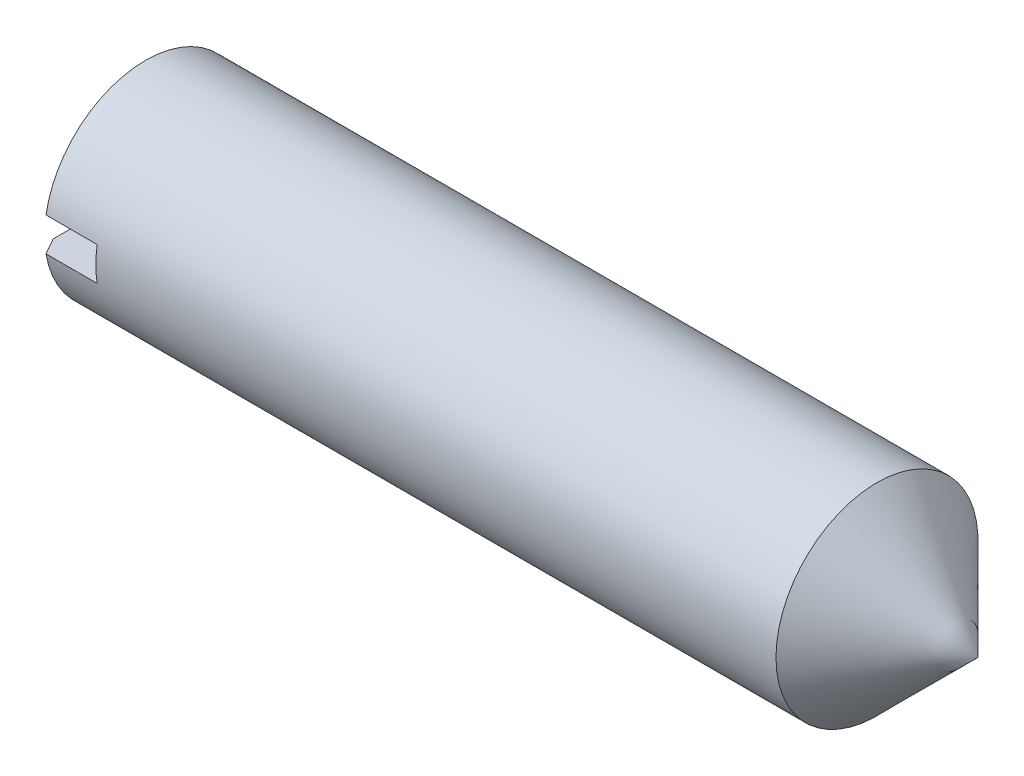
SolidWorks part; units mm, degrees
revolve "BaseBody" add sketch "BodySke"
sketch "BodySke" plane through (0, 0, 0) normal (0, 0, 1) x (1, 0, 0)
  line L0 (0, 0) -> (0, 5.036)
  line L1 (0, 5.036) -> (0.5566, 6)
  line L2 (0.5566, 6) -> (44, 6)
  line L3 (44, 6) -> (50, 0)
  line L4 (50, 0) -> (0, 0)
  line L5 (-12.7, 0) -> (88.9, 0) construction
  line L6 (44, -6) -> (50, 0) construction
  line L7 (0.875, 15.875) -> (0.875, -3.175) construction
  line L8 (0, -5.036) -> (0.5566, -6) construction
  dimension "Diameter" = 12
  dimension "Drive_ch_ang" = 60
  dimension "Minor_dia" = 10.072
  dimension "Advance" = 1.75
  dimension "Cone_ang" = 90
  dimension "Length" = 50
cosmetic thread "ThreadCosmetic" [suppressed]
extrude "Slot" cut sketch "Sketch2" against normal blind 3.6
sketch "Sketch2" plane through (0, 0, 0) normal (-1, 0, 0) x (0, 0, 1)
  line L0 (6, 1) -> (-6, 1)
  line L1 (6, -1) -> (6, 1)
  line L2 (-6, -1) -> (-6, 1)
  line L4 (6, -1) -> (-6, -1)
  circle A2 centre (0, 0) radius 6 construction
  dimension "D1" = 1
  dimension "Slot_width" = 2
ref_plane "Plane1" through (0, 0, 0) normal (0, 0, 1) x (1, 0, 0)
ref_plane "Plane2" through (0, 0, 0) normal (0, 1, 0) x (1, 0, 0)
ref_plane "Plane3" through (0, 0, 0) normal (1, 0, 0) x (0, 0, -1)
sketch "ThdSchSke" plane through (0, 0, 0) normal (0, 0, 1) x (1, 0, 0)
  line L0 (0.5566, -5.036) -> (-0.1184, -6)
  line L1 (0.5566, -5.036) -> (1.2316, -6)
  line L2 (1.2316, -6) -> (1.2316, -7.5)
  line L3 (-3.175, 0) -> (5.1513, 0) construction
  line L4 (0.5566, 6) -> (0.5566, -6) construction
  line L5 (1.2316, -7.5) -> (-0.1184, -7.5)
  line L6 (-0.1184, -7.5) -> (-0.1184, -6)
  dimension "Thread_minor" = 10.072
  dimension "Diameter" = 12
revolve "ThreadSchematic" [suppressed] cut sketch "ThdSchSke" angle 360 about L3
pattern_linear "ThdSchPat" [suppressed]
equation "\"Thread_minor@ThreadCosmetic\" = \"Minor_dia@BodySke\""
equation "\"Thread_minor@ThdSchSke\" = \"Thread_minor@ThreadCosmetic\""
equation "\"Diameter@ThdSchSke\" = \"Diameter@BodySke\""
equation "\"Overcut@ThdSchSke\" = \"Diameter@BodySke\" * 1.25"
equation "\"Num_threads@ThdSchPat\" = int( (\"Length@BodySke\" - ( ( ( \"Diameter@BodySke\" - \"Minor_dia@BodySke\" ) * 0.5 ) / tan( \"Drive_ch_ang@BodySke\" * 0.017453292 ) ) - ( ( \"Diameter@BodySke\" * 0.5 ) / tan( \"Cone_ang@BodySke\" * 0.008726646 ) ) ) / \"Advance@BodySke\" + 0.999 )  + 1"
equation "\"Advance@ThdSchPat\" = (\"Length@BodySke\" - ( ( ( \"Diameter@BodySke\" - \"Minor_dia@BodySke\" ) * 0.5 ) / tan( \"Drive_ch_ang@BodySke\" * 0.017453292 ) ) - ( ( \"Diameter@BodySke\" * 0.5 ) / tan( \"Cone_ang@BodySke\" * 0.008726646 ) ) ) /  (\"Num_threads@ThdSchPat\" - 1) 'relax it"
equation "' \"Num_threads@ThdSchPat\" = \"Num_threads@ThdSchPat\" - sgn( \"Num_threads@ThdSchPat\" - 1) '---chamfered tips only---"
equation "\"D1@Sketch2\" = \"Slot_width@Sketch2\" / 2"
